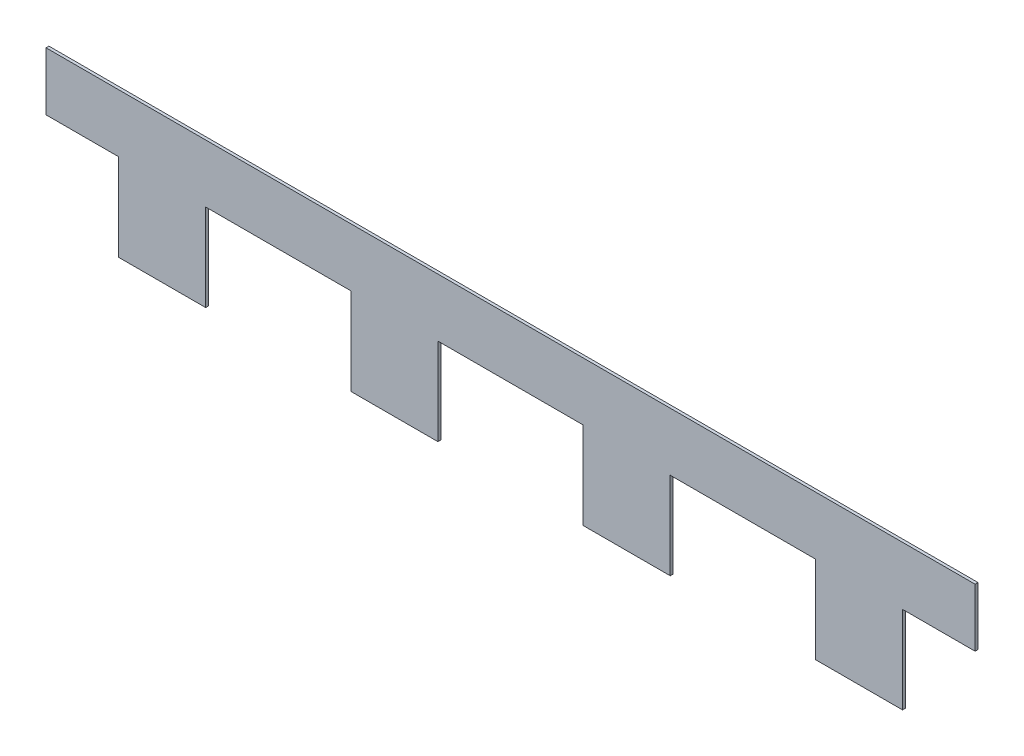
SolidWorks part; units mm, degrees
ref_plane "Front Plane" through (0, 0, 0) normal (0, 0, 1) x (1, 0, 0)
ref_plane "Top Plane" through (0, 0, 0) normal (0, 1, 0) x (1, 0, 0)
ref_plane "Right Plane" through (0, 0, 0) normal (1, 0, 0) x (0, 0, -1)
sketch "Sketch1" plane through (0, 0, 0) normal (0, 0, 1) x (1, 0, 0)
  line L0 (6.5, -4) -> (9.5, -4)
  line L1 (-4, 1) -> (28, 1)
  line L2 (-4, 1) -> (-4, -1)
  line L3 (-4, -1) -> (-1.5, -1)
  line L4 (28, 1) -> (28, -1)
  line L6 (-1.5, -1) -> (-1.5, -4)
  line L7 (-1.5, -4) -> (1.5, -4)
  line L8 (1.5, -1) -> (1.5, -4)
  line L9 (9.5, -1) -> (9.5, -4)
  line L10 (6.5, -1) -> (6.5, -4)
  line L11 (14.5, -4) -> (17.5, -4)
  line L12 (17.5, -1) -> (17.5, -4)
  line L13 (14.5, -1) -> (14.5, -4)
  line L14 (22.5, -4) -> (25.5, -4)
  line L15 (25.5, -1) -> (25.5, -4)
  line L16 (22.5, -1) -> (22.5, -4)
  line L17 (9.5, -1) -> (14.5, -1)
  line L18 (17.5, -1) -> (22.5, -1)
  line L19 (25.5, -1) -> (28, -1)
  line L20 (1.5, -1) -> (6.5, -1)
  dimension "D1" = 4
  dimension "D2" = 2
  dimension "D3" = 1
  dimension "D4" = 32
  dimension "D5" = 1.5
  dimension "D6" = 1.5
  dimension "D7" = 3
  dimension "D9" = 5
  dimension "D8" = 4
extrude "Boss-Extrude1" add sketch "Sketch1" along normal blind 0.1
